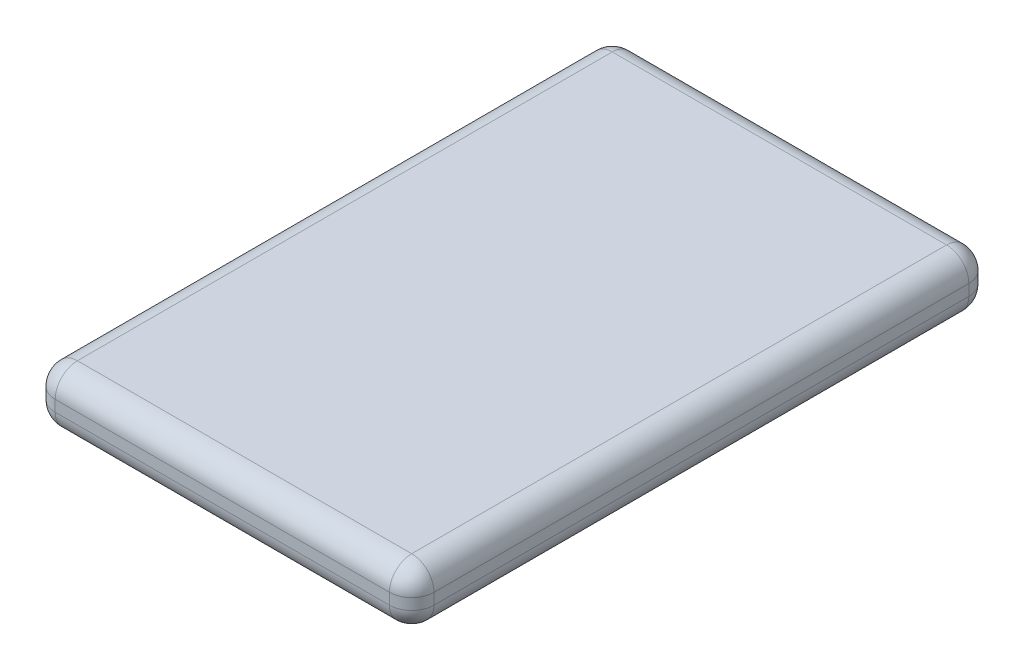
SolidWorks part; units mm, degrees
ref_plane "Front Plane" through (0, 0, 0) normal (0, 0, 1) x (1, 0, 0)
ref_plane "Top Plane" through (0, 0, 0) normal (0, 1, 0) x (1, 0, 0)
ref_plane "Right Plane" through (0, 0, 0) normal (1, 0, 0) x (0, 0, -1)
sketch "Sketch1" plane through (0, 0, 0) normal (0, 1, 0) x (1, 0, 0)
  line L1 (0, 0) -> (34, 0)
  line L2 (0, 0) -> (0, 52)
  line L3 (0, 52) -> (34, 52)
  line L4 (34, 0) -> (34, 52)
  dimension "D1" = 34
  dimension "D2" = 52
extrude "Boss-Extrude1" add sketch "Sketch1" along normal blind 5
fillet "Fillet1" radius 2 12 edges at (34, 5, -26) (34, 0, -26) (17, 5, 0) (34, 2.5, 0) (17, 0, 0) (0, 5, -26) (0, 2.5, 0) (0, 0, -26) (34, 2.5, -52) (17, 5, -52) (0, 2.5, -52) (17, 0, -52)
